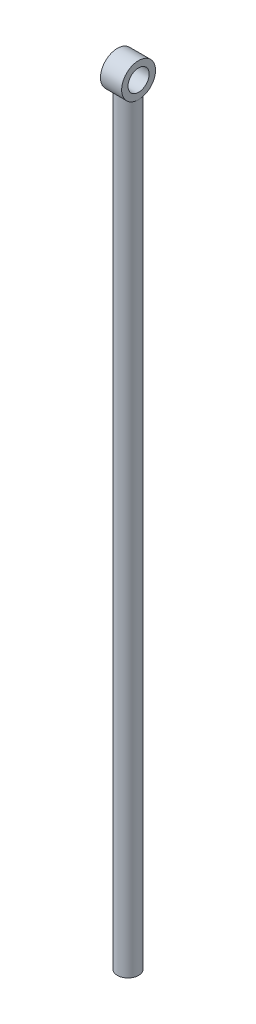
SolidWorks part; units mm, degrees
ref_plane "Front Plane" through (0, 0, 0) normal (0, 0, 1) x (1, 0, 0)
ref_plane "Top Plane" through (0, 0, 0) normal (0, 1, 0) x (1, 0, 0)
ref_plane "Right Plane" through (0, 0, 0) normal (1, 0, 0) x (0, 0, -1)
sketch "Sketch1" plane through (0, 0, 0) normal (0, 1, 0) x (1, 0, 0)
  circle A0 centre (0, 0) radius 5
  dimension "D1" = 10
extrude "Boss-Extrude1" add sketch "Sketch1" along normal blind 360
sketch "Sketch2" plane through (0, 0, 0) normal (1, 0, 0) x (0, 0, -1)
  circle A0 centre (0, 366.245) radius 8
  circle A1 centre (0, 366.245) radius 5
  dimension "D1" = 16
  dimension "D2" = 10
extrude "Boss-Extrude2" add sketch "Sketch2" along normal mid plane 10
